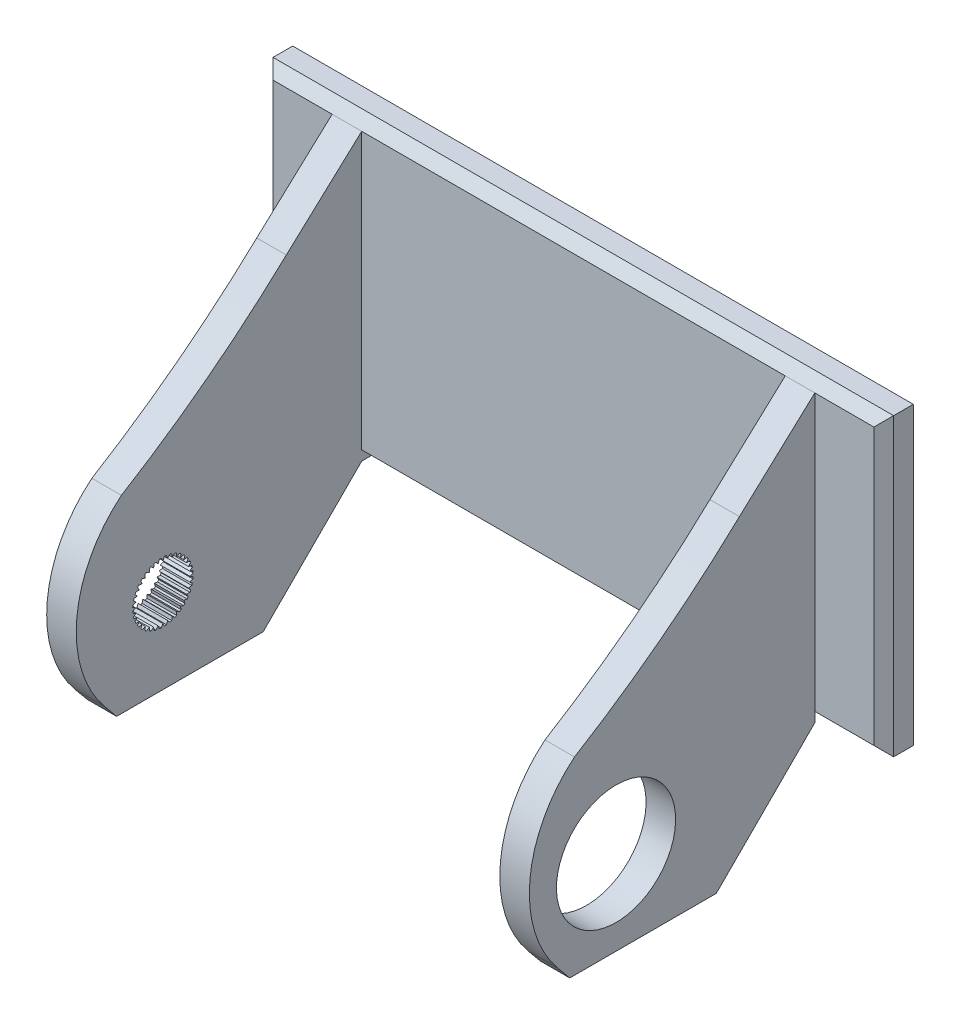
SolidWorks part; units mm, degrees
material "PLA"
ref_plane "Front Plane" through (0, 0, 0) normal (0, 0, 1) x (1, 0, 0)
ref_plane "Top Plane" through (0, 0, 0) normal (0, 1, 0) x (1, 0, 0)
ref_plane "Right Plane" through (0, 0, 0) normal (1, 0, 0) x (0, 0, -1)
sketch "Sketch2" plane through (0, 0, 0) normal (0, 0, 1) x (1, 0, 0)
  line L1 (-31.5, -15) -> (31.5, -15)
  line L2 (-31.5, -15) -> (-31.5, 15)
  line L3 (-31.5, 15) -> (31.5, 15)
  line L4 (31.5, -15) -> (31.5, 15)
  point P4 (0, 15)
  point P6 (-31.5, 0)
  dimension "D1" = 63
  dimension "D2" = 30
extrude "Boss-Extrude2" add sketch "Sketch2" along normal blind 3
sketch "Sketch6" plane through (0, 0, 3) normal (0, 0, 1) x (1, 0, 0)
  line L0 (31.5, 15) -> (-31.5, 15) construction
  line L1 (-24.5, 15) -> (-21.5, 15)
  line L3 (-24.5, -15) -> (-21.5, -15)
  line L4 (-21.5, 15) -> (-21.5, -15)
  line L5 (-31.5, -15) -> (31.5, -15) construction
  line L7 (-24.5, 15) -> (-24.5, -15)
  dimension "D1" = 3
extrude "Boss-Extrude5" add sketch "Sketch6" along normal blind 20
sketch "Sketch7" plane through (0, -15, 0) normal (0, -1, 0) x (1, 0, 0)
  line L0 (-31.5, 0) -> (31.5, 0) construction
  line L1 (-24.5, 23) -> (-21.5, 23)
  line L2 (-24.5, 23) -> (-24.5, 0)
  line L3 (-24.5, 0) -> (-21.5, 0)
  line L4 (-21.5, 23) -> (-21.5, 0)
  dimension "D1" = 3
extrude "Boss-Extrude6" add sketch "Sketch7" along normal blind 10
sketch "Sketch8" plane through (0, 0, 23) normal (0, 0, 1) x (1, 0, 0)
  line L4 (-24.5, 15) -> (-24.5, -25)
  line L5 (-24.5, 15) -> (-24.5, -25)
  line L7 (-24.5, -25) -> (-21.5, -25)
  line L8 (-21.5, -25) -> (-21.5, 15)
  line L11 (-21.5, 15) -> (-24.5, 15)
  line L13 (-24.5, -25) -> (-21.5, -25)
  line L14 (-21.5, -25) -> (-21.5, 15)
  line L17 (-21.5, 15) -> (-24.5, 15)
  dimension "D1" = 0
extrude "Boss-Extrude7" add sketch "Sketch8" along normal blind 15
sketch "Sketch9" plane through (-24.5, 0, 0) normal (-1, 0, 0) x (0, 0, 1)
  line L288 (25.551, -14.882) -> (25.5973, -14.8018) construction
  line L289 (25.5298, -14.7054) -> (25.4386, -14.7215) construction
  line L290 (25.5973, -14.8018) -> (25.6299, -14.7454) construction
  line L291 (25.5939, -14.6941) -> (25.5298, -14.7054) construction
  line L292 (25.4711, -15.0204) -> (25.551, -14.882) construction
  line L293 (25.4386, -14.7215) -> (25.2812, -14.7493) construction
  line L294 (25.279, -14.4066) -> (25.3013, -14.3454) construction
  line L295 (25.257, -14.3011) -> (25.1958, -14.3233) construction
  line L296 (25.2473, -14.4936) -> (25.279, -14.4066) construction
  line L297 (25.1958, -14.3233) -> (25.1088, -14.355) construction
  line L298 (25.1927, -14.6438) -> (25.2473, -14.4936) construction
  line L299 (25.1088, -14.355) -> (24.9586, -14.4097) construction
  line L300 (24.8569, -13.9725) -> (24.8005, -14.0051) construction
  line L301 (24.8969, -14.0726) -> (24.9082, -14.0084) construction
  line L302 (24.8005, -14.0051) -> (24.7203, -14.0514) construction
  line L303 (24.8808, -14.1638) -> (24.8969, -14.0726) construction
  line L304 (24.7203, -14.0514) -> (24.5819, -14.1313) construction
  line L305 (24.8531, -14.3211) -> (24.8808, -14.1638) construction
  line L306 (25.6799, -15.4397) -> (25.7826, -15.3173) construction
  line L307 (25.6998, -15.1397) -> (25.54, -15.1397) construction
  line L308 (25.8421, -15.2464) -> (25.884, -15.1965) construction
  line L309 (25.8575, -15.1397) -> (25.7924, -15.1397) construction
  line L310 (25.7826, -15.3173) -> (25.8421, -15.2464) construction
  line L311 (25.7924, -15.1397) -> (25.6998, -15.1397) construction
  line L312 (26.006, -15.7267) -> (26.0559, -15.6848) construction
  line L313 (26.0397, -15.6243) -> (25.9756, -15.613) construction
  line L314 (25.9351, -15.7862) -> (26.006, -15.7267) construction
  line L315 (25.9756, -15.613) -> (25.8843, -15.5969) construction
  line L316 (25.8126, -15.8889) -> (25.9351, -15.7862) construction
  line L317 (25.8843, -15.5969) -> (25.727, -15.5692) construction
  line L318 (25.8654, -16.3543) -> (26.0038, -16.2744) construction
  line L319 (25.9867, -16.0792) -> (25.8366, -16.0246) construction
  line L320 (26.0038, -16.2744) -> (26.084, -16.2281) construction
  line L321 (26.0738, -16.1109) -> (25.9867, -16.0792) construction
  line L322 (26.084, -16.2281) -> (26.1404, -16.1956) construction
  line L323 (26.1349, -16.1332) -> (26.0738, -16.1109) construction
  line L324 (26.1404, -16.6509) -> (26.084, -16.6183) construction
  line L325 (26.0738, -16.7355) -> (26.1349, -16.7133) construction
  line L326 (26.084, -16.6183) -> (26.0038, -16.572) construction
  line L327 (25.9867, -16.7672) -> (26.0738, -16.7355) construction
  line L328 (26.0038, -16.572) -> (25.8654, -16.4921) construction
  line L329 (25.8366, -16.8219) -> (25.9867, -16.7672) construction
  line L330 (25.9756, -17.2334) -> (26.0397, -17.2221) construction
  line L331 (26.0559, -17.1616) -> (26.006, -17.1198) construction
  line L332 (25.8843, -17.2495) -> (25.9756, -17.2334) construction
  line L333 (26.006, -17.1198) -> (25.9351, -17.0602) construction
  line L334 (25.727, -17.2773) -> (25.8843, -17.2495) construction
  line L335 (25.9351, -17.0602) -> (25.8126, -16.9575) construction
  line L336 (25.6998, -17.7067) -> (25.7924, -17.7067) construction
  line L337 (25.8421, -17.6001) -> (25.7826, -17.5291) construction
  line L338 (25.54, -17.7067) -> (25.6998, -17.7067) construction
  line L339 (25.7826, -17.5291) -> (25.6799, -17.4067) construction
  line L340 (25.8654, -16.4921) -> (25.7461, -16.4232) construction
  line L341 (25.7461, -16.4232) -> (25.8654, -16.3543) construction
  line L342 (25.8366, -16.0246) -> (25.7071, -15.9775) construction
  line L343 (25.7071, -15.9775) -> (25.8126, -15.8889) construction
  line L344 (25.727, -15.5692) -> (25.5913, -15.5453) construction
  line L345 (25.5913, -15.5453) -> (25.6799, -15.4397) construction
  line L346 (25.54, -15.1397) -> (25.4022, -15.1397) construction
  line L347 (25.4022, -15.1397) -> (25.4711, -15.0204) construction
  line L348 (25.2812, -14.7493) -> (25.1456, -14.7732) construction
  line L349 (25.1456, -14.7732) -> (25.1927, -14.6438) construction
  line L350 (24.9586, -14.4097) -> (24.8292, -14.4568) construction
  line L351 (24.8292, -14.4568) -> (24.8531, -14.3211) construction
  line L352 (24.5819, -14.1313) -> (24.4626, -14.2001) construction
  line L353 (24.4626, -14.2001) -> (24.4626, -14.0624) construction
  line L354 (24.1626, -13.9225) -> (24.0571, -14.011) construction
  line L355 (24.0571, -14.011) -> (24.0332, -13.8754) construction
  line L356 (23.7134, -13.7897) -> (23.6249, -13.8952) construction
  line L357 (23.6249, -13.8952) -> (23.5778, -13.7658) construction
  line L358 (23.248, -13.7369) -> (23.1791, -13.8562) construction
  line L359 (23.1791, -13.8562) -> (23.1103, -13.7369) construction
  line L360 (22.7805, -13.7658) -> (22.7334, -13.8952) construction
  line L361 (22.7334, -13.8952) -> (22.6449, -13.7897) construction
  line L362 (22.3251, -13.8754) -> (22.3012, -14.011) construction
  line L363 (22.3012, -14.011) -> (22.1957, -13.9225) construction
  line L364 (21.8957, -14.0624) -> (21.8957, -14.2001) construction
  line L365 (21.8957, -14.2001) -> (21.7764, -14.1313) construction
  line L366 (21.5052, -14.3211) -> (21.5291, -14.4568) construction
  line L367 (21.5291, -14.4568) -> (21.3997, -14.4097) construction
  line L368 (21.1656, -14.6438) -> (21.2127, -14.7732) construction
  line L369 (21.2127, -14.7732) -> (21.0771, -14.7493) construction
  line L370 (20.8872, -15.0204) -> (20.9561, -15.1397) construction
  line L371 (20.9561, -15.1397) -> (20.8183, -15.1397) construction
  line L372 (20.6784, -15.4397) -> (20.767, -15.5453) construction
  line L373 (20.767, -15.5453) -> (20.6313, -15.5692) construction
  line L374 (20.5456, -15.8889) -> (20.6512, -15.9775) construction
  line L375 (20.6512, -15.9775) -> (20.5217, -16.0246) construction
  line L376 (20.4929, -16.3543) -> (20.6122, -16.4232) construction
  line L377 (20.6122, -16.4232) -> (20.4929, -16.4921) construction
  line L378 (20.5217, -16.8219) -> (20.6512, -16.869) construction
  line L379 (20.6512, -16.869) -> (20.5456, -16.9575) construction
  line L380 (20.6313, -17.2773) -> (20.767, -17.3012) construction
  line L381 (20.767, -17.3012) -> (20.6784, -17.4067) construction
  line L382 (20.8183, -17.7067) -> (20.9561, -17.7067) construction
  line L383 (20.9561, -17.7067) -> (20.8872, -17.826) construction
  line L384 (21.0771, -18.0972) -> (21.2127, -18.0732) construction
  line L385 (21.2127, -18.0732) -> (21.1656, -18.2027) construction
  line L386 (21.3997, -18.4368) -> (21.5291, -18.3896) construction
  line L387 (21.5291, -18.3896) -> (21.5052, -18.5253) construction
  line L388 (21.7764, -18.7152) -> (21.8957, -18.6463) construction
  line L389 (21.8957, -18.6463) -> (21.8957, -18.784) construction
  line L390 (22.1957, -18.9239) -> (22.3012, -18.8354) construction
  line L391 (22.3012, -18.8354) -> (22.3251, -18.971) construction
  line L392 (22.6449, -19.0567) -> (22.7334, -18.9512) construction
  line L393 (22.7334, -18.9512) -> (22.7805, -19.0806) construction
  line L394 (23.1103, -19.1095) -> (23.1791, -18.9902) construction
  line L395 (23.1791, -18.9902) -> (23.248, -19.1095) construction
  line L396 (23.5778, -19.0806) -> (23.6249, -18.9512) construction
  line L397 (23.6249, -18.9512) -> (23.7134, -19.0567) construction
  line L398 (24.0332, -18.971) -> (24.0571, -18.8354) construction
  line L399 (24.0571, -18.8354) -> (24.1626, -18.9239) construction
  line L400 (24.4626, -18.784) -> (24.4626, -18.6463) construction
  line L401 (24.4626, -18.6463) -> (24.5819, -18.7152) construction
  line L402 (24.8531, -18.5253) -> (24.8292, -18.3896) construction
  line L403 (24.8292, -18.3896) -> (24.9586, -18.4368) construction
  line L404 (25.1927, -18.2027) -> (25.1456, -18.0732) construction
  line L405 (25.1456, -18.0732) -> (25.2812, -18.0972) construction
  line L406 (25.4711, -17.826) -> (25.4022, -17.7067) construction
  line L407 (25.4022, -17.7067) -> (25.54, -17.7067) construction
  line L408 (25.6799, -17.4067) -> (25.5913, -17.3012) construction
  line L409 (25.5913, -17.3012) -> (25.727, -17.2773) construction
  line L410 (25.8126, -16.9575) -> (25.7071, -16.869) construction
  line L411 (25.7071, -16.869) -> (25.8366, -16.8219) construction
  line L412 (25.7924, -17.7067) -> (25.8575, -17.7067) construction
  line L413 (25.884, -17.6499) -> (25.8421, -17.6001) construction
  line L414 (25.6299, -18.101) -> (25.5973, -18.0446) construction
  line L415 (25.5298, -18.141) -> (25.5939, -18.1523) construction
  line L416 (25.5973, -18.0446) -> (25.551, -17.9644) construction
  line L417 (25.4386, -18.1249) -> (25.5298, -18.141) construction
  line L418 (24.9586, -18.4368) -> (25.1088, -18.4914) construction
  line L419 (25.2473, -18.3528) -> (25.1927, -18.2027) construction
  line L420 (25.1088, -18.4914) -> (25.1958, -18.5231) construction
  line L421 (25.279, -18.4399) -> (25.2473, -18.3528) construction
  line L422 (25.1958, -18.5231) -> (25.257, -18.5454) construction
  line L423 (25.3013, -18.5011) -> (25.279, -18.4399) construction
  line L424 (25.551, -17.9644) -> (25.4711, -17.826) construction
  line L425 (25.2812, -18.0972) -> (25.4386, -18.1249) construction
  line L426 (24.9082, -18.838) -> (24.8969, -18.7739) construction
  line L427 (24.8005, -18.8414) -> (24.8569, -18.8739) construction
  line L428 (24.8969, -18.7739) -> (24.8808, -18.6827) construction
  line L429 (24.7203, -18.7951) -> (24.8005, -18.8414) construction
  line L430 (24.8808, -18.6827) -> (24.8531, -18.5253) construction
  line L431 (24.5819, -18.7152) -> (24.7203, -18.7951) construction
  line L432 (22.8668, -19.3178) -> (22.8891, -19.379) construction
  line L433 (22.9515, -19.3845) -> (22.9841, -19.3281) construction
  line L434 (22.8352, -19.2308) -> (22.8668, -19.3178) construction
  line L435 (22.9841, -19.3281) -> (23.0304, -19.2479) construction
  line L436 (23.5231, -19.2308) -> (23.5778, -19.0806) construction
  line L437 (23.248, -19.1095) -> (23.3279, -19.2479) construction
  line L438 (23.4915, -19.3178) -> (23.5231, -19.2308) construction
  line L439 (23.3279, -19.2479) -> (23.3742, -19.3281) construction
  line L440 (23.4692, -19.379) -> (23.4915, -19.3178) construction
  line L441 (23.3742, -19.3281) -> (23.4068, -19.3845) construction
  line L442 (23.8757, -19.2501) -> (23.9175, -19.3) construction
  line L443 (23.978, -19.2838) -> (23.9894, -19.2196) construction
  line L444 (24.356, -19.0862) -> (24.4059, -19.128) construction
  line L445 (24.4626, -19.1016) -> (24.4626, -19.0365) construction
  line L446 (24.285, -19.0267) -> (24.356, -19.0862) construction
  line L447 (24.4626, -19.0365) -> (24.4626, -18.9438) construction
  line L448 (24.1626, -18.9239) -> (24.285, -19.0267) construction
  line L449 (24.4626, -18.9438) -> (24.4626, -18.784) construction
  line L450 (23.8162, -19.1791) -> (23.8757, -19.2501) construction
  line L451 (23.9894, -19.2196) -> (24.0054, -19.1284) construction
  line L452 (23.7134, -19.0567) -> (23.8162, -19.1791) construction
  line L453 (24.0054, -19.1284) -> (24.0332, -18.971) construction
  line L454 (22.7805, -19.0806) -> (22.8352, -19.2308) construction
  line L455 (23.0304, -19.2479) -> (23.1103, -19.1095) construction
  line L456 (22.3689, -19.2196) -> (22.3802, -19.2838) construction
  line L457 (22.4407, -19.3) -> (22.4826, -19.2501) construction
  line L458 (22.3529, -19.1284) -> (22.3689, -19.2196) construction
  line L459 (22.4826, -19.2501) -> (22.5421, -19.1791) construction
  line L460 (22.3251, -18.971) -> (22.3529, -19.1284) construction
  line L461 (22.5421, -19.1791) -> (22.6449, -19.0567) construction
  line L462 (21.8957, -19.0365) -> (21.8957, -19.1016) construction
  line L463 (21.9524, -19.128) -> (22.0023, -19.0862) construction
  line L464 (21.8957, -18.9438) -> (21.8957, -19.0365) construction
  line L465 (22.0023, -19.0862) -> (22.0733, -19.0267) construction
  line L466 (21.8957, -18.784) -> (21.8957, -18.9438) construction
  line L467 (22.0733, -19.0267) -> (22.1957, -18.9239) construction
  line L468 (21.4614, -18.7739) -> (21.4501, -18.838) construction
  line L469 (21.5014, -18.8739) -> (21.5578, -18.8414) construction
  line L470 (21.4775, -18.6827) -> (21.4614, -18.7739) construction
  line L471 (21.5578, -18.8414) -> (21.638, -18.7951) construction
  line L472 (21.5052, -18.5253) -> (21.4775, -18.6827) construction
  line L473 (21.638, -18.7951) -> (21.7764, -18.7152) construction
  line L474 (21.0793, -18.4399) -> (21.057, -18.5011) construction
  line L475 (21.1013, -18.5454) -> (21.1625, -18.5231) construction
  line L476 (21.111, -18.3528) -> (21.0793, -18.4399) construction
  line L477 (21.1625, -18.5231) -> (21.2495, -18.4914) construction
  line L478 (21.1656, -18.2027) -> (21.111, -18.3528) construction
  line L479 (21.2495, -18.4914) -> (21.3997, -18.4368) construction
  line L480 (20.7644, -18.1523) -> (20.8285, -18.141) construction
  line L481 (20.761, -18.0446) -> (20.7284, -18.101) construction
  line L482 (20.8285, -18.141) -> (20.9197, -18.1249) construction
  line L483 (20.8073, -17.9644) -> (20.761, -18.0446) construction
  line L484 (20.9197, -18.1249) -> (21.0771, -18.0972) construction
  line L485 (20.8872, -17.826) -> (20.8073, -17.9644) construction
  line L486 (20.5008, -17.7067) -> (20.5659, -17.7067) construction
  line L487 (20.5162, -17.6001) -> (20.4743, -17.6499) construction
  line L488 (20.5659, -17.7067) -> (20.6585, -17.7067) construction
  line L489 (20.5757, -17.5291) -> (20.5162, -17.6001) construction
  line L490 (20.6585, -17.7067) -> (20.8183, -17.7067) construction
  line L491 (20.6784, -17.4067) -> (20.5757, -17.5291) construction
  line L492 (20.3186, -17.2221) -> (20.3827, -17.2334) construction
  line L493 (20.3523, -17.1198) -> (20.3024, -17.1616) construction
  line L494 (20.3827, -17.2334) -> (20.4739, -17.2495) construction
  line L495 (20.4232, -17.0602) -> (20.3523, -17.1198) construction
  line L496 (20.4739, -17.2495) -> (20.6313, -17.2773) construction
  line L497 (20.5456, -16.9575) -> (20.4232, -17.0602) construction
  line L498 (20.2233, -16.7133) -> (20.2845, -16.7355) construction
  line L499 (20.2743, -16.6183) -> (20.2179, -16.6509) construction
  line L500 (20.3716, -16.7672) -> (20.5217, -16.8219) construction
  line L501 (20.4929, -16.4921) -> (20.3545, -16.572) construction
  line L502 (20.2845, -16.7355) -> (20.3716, -16.7672) construction
  line L503 (20.3545, -16.572) -> (20.2743, -16.6183) construction
  line L504 (20.2179, -16.1956) -> (20.2743, -16.2281) construction
  line L505 (20.2845, -16.1109) -> (20.2233, -16.1332) construction
  line L506 (20.2743, -16.2281) -> (20.3545, -16.2744) construction
  line L507 (20.3716, -16.0792) -> (20.2845, -16.1109) construction
  line L508 (20.3545, -16.2744) -> (20.4929, -16.3543) construction
  line L509 (20.5217, -16.0246) -> (20.3716, -16.0792) construction
  line L510 (20.3523, -15.7267) -> (20.4232, -15.7862) construction
  line L511 (20.4739, -15.5969) -> (20.3827, -15.613) construction
  line L512 (20.3024, -15.6848) -> (20.3523, -15.7267) construction
  line L513 (20.3827, -15.613) -> (20.3186, -15.6243) construction
  line L514 (20.4232, -15.7862) -> (20.5456, -15.8889) construction
  line L515 (20.6313, -15.5692) -> (20.4739, -15.5969) construction
  line L516 (20.5162, -15.2464) -> (20.5757, -15.3173) construction
  line L517 (20.6585, -15.1397) -> (20.5659, -15.1397) construction
  line L518 (20.4743, -15.1965) -> (20.5162, -15.2464) construction
  line L519 (20.5659, -15.1397) -> (20.5008, -15.1397) construction
  line L520 (20.5757, -15.3173) -> (20.6784, -15.4397) construction
  line L521 (20.8183, -15.1397) -> (20.6585, -15.1397) construction
  line L522 (20.7284, -14.7454) -> (20.761, -14.8018) construction
  line L523 (20.8285, -14.7054) -> (20.7644, -14.6941) construction
  line L524 (20.761, -14.8018) -> (20.8073, -14.882) construction
  line L525 (20.9197, -14.7215) -> (20.8285, -14.7054) construction
  line L526 (20.8073, -14.882) -> (20.8872, -15.0204) construction
  line L527 (21.0771, -14.7493) -> (20.9197, -14.7215) construction
  line L528 (21.1625, -14.3233) -> (21.1013, -14.3011) construction
  line L529 (21.057, -14.3454) -> (21.0793, -14.4066) construction
  line L530 (21.2495, -14.355) -> (21.1625, -14.3233) construction
  line L531 (21.0793, -14.4066) -> (21.111, -14.4936) construction
  line L532 (21.3997, -14.4097) -> (21.2495, -14.355) construction
  line L533 (21.111, -14.4936) -> (21.1656, -14.6438) construction
  line L534 (21.4501, -14.0084) -> (21.4614, -14.0726) construction
  line L535 (21.5578, -14.0051) -> (21.5014, -13.9725) construction
  line L536 (21.4614, -14.0726) -> (21.4775, -14.1638) construction
  line L537 (21.638, -14.0514) -> (21.5578, -14.0051) construction
  line L538 (21.4775, -14.1638) -> (21.5052, -14.3211) construction
  line L539 (21.7764, -14.1313) -> (21.638, -14.0514) construction
  line L540 (21.8957, -13.7449) -> (21.8957, -13.81) construction
  line L541 (22.0023, -13.7602) -> (21.9524, -13.7184) construction
  line L542 (21.8957, -13.81) -> (21.8957, -13.9026) construction
  line L543 (22.0733, -13.8198) -> (22.0023, -13.7602) construction
  line L544 (21.8957, -13.9026) -> (21.8957, -14.0624) construction
  line L545 (22.1957, -13.9225) -> (22.0733, -13.8198) construction
  line L546 (22.3802, -13.5627) -> (22.3689, -13.6268) construction
  line L547 (22.4826, -13.5963) -> (22.4407, -13.5465) construction
  line L548 (22.3689, -13.6268) -> (22.3529, -13.718) construction
  line L549 (22.5421, -13.6673) -> (22.4826, -13.5963) construction
  line L550 (22.3529, -13.718) -> (22.3251, -13.8754) construction
  line L551 (22.6449, -13.7897) -> (22.5421, -13.6673) construction
  line L552 (24.356, -13.7602) -> (24.285, -13.8198) construction
  line L553 (24.4626, -13.9026) -> (24.4626, -13.81) construction
  line L554 (24.4059, -13.7184) -> (24.356, -13.7602) construction
  line L555 (24.4626, -13.81) -> (24.4626, -13.7449) construction
  line L556 (24.285, -13.8198) -> (24.1626, -13.9225) construction
  line L557 (24.4626, -14.0624) -> (24.4626, -13.9026) construction
  line L558 (23.9894, -13.6268) -> (23.978, -13.5627) construction
  line L559 (23.9175, -13.5465) -> (23.8757, -13.5963) construction
  line L560 (24.0054, -13.718) -> (23.9894, -13.6268) construction
  line L561 (23.8757, -13.5963) -> (23.8162, -13.6673) construction
  line L562 (24.0332, -13.8754) -> (24.0054, -13.718) construction
  line L563 (23.8162, -13.6673) -> (23.7134, -13.7897) construction
  line L564 (23.4915, -13.5286) -> (23.4692, -13.4674) construction
  line L565 (23.4068, -13.462) -> (23.3742, -13.5183) construction
  line L566 (23.5231, -13.6156) -> (23.4915, -13.5286) construction
  line L567 (23.3742, -13.5183) -> (23.3279, -13.5986) construction
  line L568 (23.5778, -13.7658) -> (23.5231, -13.6156) construction
  line L569 (23.3279, -13.5986) -> (23.248, -13.7369) construction
  line L570 (22.8891, -13.4674) -> (22.8668, -13.5286) construction
  line L571 (22.9841, -13.5183) -> (22.9515, -13.462) construction
  line L572 (22.8668, -13.5286) -> (22.8352, -13.6156) construction
  line L573 (23.0304, -13.5986) -> (22.9841, -13.5183) construction
  line L574 (22.8352, -13.6156) -> (22.7805, -13.7658) construction
  line L575 (23.1103, -13.7369) -> (23.0304, -13.5986) construction
  line L576 (25.6376, -14.932) -> (25.6839, -14.8518)
  line L577 (25.6839, -14.8518) -> (25.7476, -14.7415)
  line L578 (25.6379, -14.5848) -> (25.5124, -14.607)
  line L579 (25.5124, -14.607) -> (25.4212, -14.623)
  line L580 (25.4212, -14.623) -> (25.2988, -14.6446)
  line L581 (25.2988, -14.6446) -> (25.3413, -14.5278)
  line L582 (25.3413, -14.5278) -> (25.373, -14.4408)
  line L583 (25.373, -14.4408) -> (25.4165, -14.3211)
  line L584 (25.2813, -14.1858) -> (25.1616, -14.2294)
  line L585 (25.1616, -14.2294) -> (25.0746, -14.2611)
  line L586 (25.0746, -14.2611) -> (24.9577, -14.3036)
  line L587 (24.9577, -14.3036) -> (24.9793, -14.1811)
  line L588 (24.9793, -14.1811) -> (24.9954, -14.0899)
  line L589 (24.9954, -14.0899) -> (25.0175, -13.9645)
  line L590 (24.8608, -13.8548) -> (24.7505, -13.9185)
  line L591 (24.7505, -13.9185) -> (24.6703, -13.9648)
  line L592 (24.6703, -13.9648) -> (24.5626, -14.0269)
  line L593 (24.5626, -14.0269) -> (24.5626, -13.9026)
  line L594 (24.5626, -13.9026) -> (24.5626, -13.81)
  line L595 (24.5626, -13.81) -> (24.5626, -13.6826)
  line L596 (24.3893, -13.6018) -> (24.2917, -13.6836)
  line L597 (24.2917, -13.6836) -> (24.2208, -13.7432)
  line L598 (24.2208, -13.7432) -> (24.1255, -13.8231)
  line L599 (24.1255, -13.8231) -> (24.1039, -13.7007)
  line L600 (24.1039, -13.7007) -> (24.0878, -13.6094)
  line L601 (24.0878, -13.6094) -> (24.0657, -13.484)
  line L602 (23.8809, -13.4345) -> (23.7991, -13.5321)
  line L603 (23.7991, -13.5321) -> (23.7395, -13.603)
  line L604 (23.7395, -13.603) -> (23.6596, -13.6983)
  line L605 (23.6596, -13.6983) -> (23.6171, -13.5814)
  line L606 (23.6171, -13.5814) -> (23.5854, -13.4944)
  line L607 (23.5854, -13.4944) -> (23.5419, -13.3747)
  line L608 (23.3513, -13.358) -> (23.2876, -13.4683)
  line L609 (23.2876, -13.4683) -> (23.2413, -13.5486)
  line L610 (23.2413, -13.5486) -> (23.1791, -13.6562)
  line L611 (23.1791, -13.6562) -> (23.117, -13.5486)
  line L612 (23.117, -13.5486) -> (23.0707, -13.4683)
  line L613 (23.0707, -13.4683) -> (23.007, -13.358)
  line L614 (22.8164, -13.3747) -> (22.7729, -13.4944)
  line L615 (22.7729, -13.4944) -> (22.7412, -13.5814)
  line L616 (22.7412, -13.5814) -> (22.6987, -13.6983)
  line L617 (22.6987, -13.6983) -> (22.6187, -13.603)
  line L618 (22.6187, -13.603) -> (22.5592, -13.5321)
  line L619 (22.5592, -13.5321) -> (22.4773, -13.4345)
  line L620 (22.2926, -13.484) -> (22.2705, -13.6094)
  line L621 (22.2705, -13.6094) -> (22.2544, -13.7007)
  line L622 (22.2544, -13.7007) -> (22.2328, -13.8231)
  line L623 (22.2328, -13.8231) -> (22.1375, -13.7432)
  line L624 (22.1375, -13.7432) -> (22.0666, -13.6836)
  line L625 (22.0666, -13.6836) -> (21.969, -13.6018)
  line L626 (21.7957, -13.6826) -> (21.7957, -13.81)
  line L627 (21.7957, -13.81) -> (21.7957, -13.9026)
  line L628 (21.7957, -13.9026) -> (21.7957, -14.0269)
  line L629 (21.7957, -14.0269) -> (21.688, -13.9648)
  line L630 (21.688, -13.9648) -> (21.6078, -13.9185)
  line L631 (21.6078, -13.9185) -> (21.4975, -13.8548)
  line L632 (21.3408, -13.9645) -> (21.3629, -14.0899)
  line L633 (21.3629, -14.0899) -> (21.379, -14.1811)
  line L634 (21.379, -14.1811) -> (21.4006, -14.3036)
  line L635 (21.4006, -14.3036) -> (21.2837, -14.2611)
  line L636 (21.2837, -14.2611) -> (21.1967, -14.2294)
  line L637 (21.1967, -14.2294) -> (21.077, -14.1858)
  line L638 (20.9417, -14.3211) -> (20.9853, -14.4408)
  line L639 (20.9853, -14.4408) -> (21.017, -14.5278)
  line L640 (21.017, -14.5278) -> (21.0595, -14.6446)
  line L641 (21.0595, -14.6446) -> (20.9371, -14.623)
  line L642 (20.9371, -14.623) -> (20.8458, -14.607)
  line L643 (20.8458, -14.607) -> (20.7204, -14.5848)
  line L644 (20.6107, -14.7415) -> (20.6744, -14.8518)
  line L645 (20.6744, -14.8518) -> (20.7207, -14.932)
  line L646 (20.7207, -14.932) -> (20.7829, -15.0397)
  line L647 (20.7829, -15.0397) -> (20.6585, -15.0397)
  line L648 (20.6585, -15.0397) -> (20.5659, -15.0397)
  line L649 (20.5659, -15.0397) -> (20.4386, -15.0397)
  line L650 (20.3577, -15.2131) -> (20.4396, -15.3107)
  line L651 (20.4396, -15.3107) -> (20.4991, -15.3816)
  line L652 (20.4991, -15.3816) -> (20.579, -15.4769)
  line L653 (20.579, -15.4769) -> (20.4566, -15.4984)
  line L654 (20.4566, -15.4984) -> (20.3654, -15.5145)
  line L655 (20.3654, -15.5145) -> (20.2399, -15.5366)
  line L656 (20.1904, -15.7214) -> (20.288, -15.8033)
  line L657 (20.288, -15.8033) -> (20.3589, -15.8628)
  line L658 (20.3589, -15.8628) -> (20.4542, -15.9427)
  line L659 (20.4542, -15.9427) -> (20.3374, -15.9853)
  line L660 (20.3374, -15.9853) -> (20.2503, -16.0169)
  line L661 (20.2503, -16.0169) -> (20.1306, -16.0605)
  line L662 (20.114, -16.2511) -> (20.2243, -16.3147)
  line L663 (20.2243, -16.3147) -> (20.3045, -16.3611)
  line L664 (20.3045, -16.3611) -> (20.4122, -16.4232)
  line L665 (20.4122, -16.4232) -> (20.3045, -16.4854)
  line L666 (20.3045, -16.4854) -> (20.2243, -16.5317)
  line L667 (20.2243, -16.5317) -> (20.114, -16.5954)
  line L668 (20.1306, -16.7859) -> (20.2503, -16.8295)
  line L669 (20.2503, -16.8295) -> (20.3374, -16.8612)
  line L670 (20.3374, -16.8612) -> (20.4542, -16.9037)
  line L671 (20.4542, -16.9037) -> (20.3589, -16.9836)
  line L672 (20.3589, -16.9836) -> (20.288, -17.0432)
  line L673 (20.288, -17.0432) -> (20.1904, -17.125)
  line L674 (20.2399, -17.3098) -> (20.3654, -17.3319)
  line L675 (20.3654, -17.3319) -> (20.4566, -17.348)
  line L676 (20.4566, -17.348) -> (20.579, -17.3696)
  line L677 (20.579, -17.3696) -> (20.4991, -17.4648)
  line L678 (20.4991, -17.4648) -> (20.4396, -17.5358)
  line L679 (20.4396, -17.5358) -> (20.3577, -17.6333)
  line L680 (20.4386, -17.8067) -> (20.5659, -17.8067)
  line L681 (20.5659, -17.8067) -> (20.6585, -17.8067)
  line L682 (20.6585, -17.8067) -> (20.7829, -17.8067)
  line L683 (20.7829, -17.8067) -> (20.7207, -17.9144)
  line L684 (20.7207, -17.9144) -> (20.6744, -17.9946)
  line L685 (20.6744, -17.9946) -> (20.6107, -18.1049)
  line L686 (20.7204, -18.2616) -> (20.8458, -18.2395)
  line L687 (20.8458, -18.2395) -> (20.9371, -18.2234)
  line L688 (20.9371, -18.2234) -> (21.0595, -18.2018)
  line L689 (21.0595, -18.2018) -> (21.017, -18.3186)
  line L690 (21.017, -18.3186) -> (20.9853, -18.4057)
  line L691 (20.9853, -18.4057) -> (20.9417, -18.5253)
  line L692 (21.077, -18.6606) -> (21.1967, -18.6171)
  line L693 (21.1967, -18.6171) -> (21.2837, -18.5854)
  line L694 (21.2837, -18.5854) -> (21.4006, -18.5429)
  line L695 (21.4006, -18.5429) -> (21.379, -18.6653)
  line L696 (21.379, -18.6653) -> (21.3629, -18.7565)
  line L697 (21.3629, -18.7565) -> (21.3408, -18.8819)
  line L698 (21.4975, -18.9917) -> (21.6078, -18.928)
  line L699 (21.6078, -18.928) -> (21.688, -18.8817)
  line L700 (21.688, -18.8817) -> (21.7957, -18.8195)
  line L701 (21.7957, -18.8195) -> (21.7957, -18.9438)
  line L702 (21.7957, -18.9438) -> (21.7957, -19.0365)
  line L703 (21.7957, -19.0365) -> (21.7957, -19.1638)
  line L704 (21.969, -19.2447) -> (22.0666, -19.1628)
  line L705 (22.0666, -19.1628) -> (22.1375, -19.1033)
  line L706 (22.1375, -19.1033) -> (22.2328, -19.0233)
  line L707 (22.2328, -19.0233) -> (22.2544, -19.1458)
  line L708 (22.2544, -19.1458) -> (22.2705, -19.237)
  line L709 (22.2705, -19.237) -> (22.2926, -19.3624)
  line L710 (22.4773, -19.4119) -> (22.5592, -19.3144)
  line L711 (22.5592, -19.3144) -> (22.6187, -19.2434)
  line L712 (22.6187, -19.2434) -> (22.6987, -19.1482)
  line L713 (22.6987, -19.1482) -> (22.7412, -19.265)
  line L714 (22.7412, -19.265) -> (22.7729, -19.352)
  line L715 (22.7729, -19.352) -> (22.8164, -19.4717)
  line L716 (23.007, -19.4884) -> (23.0707, -19.3781)
  line L717 (23.0707, -19.3781) -> (23.117, -19.2979)
  line L718 (23.117, -19.2979) -> (23.1791, -19.1902)
  line L719 (23.1791, -19.1902) -> (23.2413, -19.2979)
  line L720 (23.2413, -19.2979) -> (23.2876, -19.3781)
  line L721 (23.2876, -19.3781) -> (23.3513, -19.4884)
  line L722 (23.5419, -19.4717) -> (23.5854, -19.352)
  line L723 (23.5854, -19.352) -> (23.6171, -19.265)
  line L724 (23.6171, -19.265) -> (23.6596, -19.1482)
  line L725 (23.6596, -19.1482) -> (23.7395, -19.2434)
  line L726 (23.7395, -19.2434) -> (23.7991, -19.3144)
  line L727 (23.7991, -19.3144) -> (23.8809, -19.4119)
  line L728 (24.0657, -19.3624) -> (24.0878, -19.237)
  line L729 (24.0878, -19.237) -> (24.1039, -19.1458)
  line L730 (24.1039, -19.1458) -> (24.1255, -19.0233)
  line L731 (24.1255, -19.0233) -> (24.2208, -19.1033)
  line L732 (24.2208, -19.1033) -> (24.2917, -19.1628)
  line L733 (24.2917, -19.1628) -> (24.3893, -19.2447)
  line L734 (24.5626, -19.1638) -> (24.5626, -19.0365)
  line L735 (24.5626, -19.0365) -> (24.5626, -18.9438)
  line L736 (24.5626, -18.9438) -> (24.5626, -18.8195)
  line L737 (24.5626, -18.8195) -> (24.6703, -18.8817)
  line L738 (24.6703, -18.8817) -> (24.7505, -18.928)
  line L739 (24.7505, -18.928) -> (24.8608, -18.9917)
  line L740 (25.0175, -18.8819) -> (24.9954, -18.7565)
  line L741 (24.9954, -18.7565) -> (24.9793, -18.6653)
  line L742 (24.9793, -18.6653) -> (24.9577, -18.5429)
  line L743 (24.9577, -18.5429) -> (25.0746, -18.5854)
  line L744 (25.0746, -18.5854) -> (25.1616, -18.6171)
  line L745 (25.1616, -18.6171) -> (25.2813, -18.6606)
  line L746 (25.4165, -18.5253) -> (25.373, -18.4057)
  line L747 (25.373, -18.4057) -> (25.3413, -18.3186)
  line L748 (25.3413, -18.3186) -> (25.2988, -18.2018)
  line L749 (25.2988, -18.2018) -> (25.4212, -18.2234)
  line L750 (25.4212, -18.2234) -> (25.5124, -18.2395)
  line L751 (25.5124, -18.2395) -> (25.6379, -18.2616)
  line L752 (25.7476, -18.1049) -> (25.6839, -17.9946)
  line L753 (25.6839, -17.9946) -> (25.6376, -17.9144)
  line L754 (25.6376, -17.9144) -> (25.5754, -17.8067)
  line L755 (25.5754, -17.8067) -> (25.6998, -17.8067)
  line L756 (25.6998, -17.8067) -> (25.7924, -17.8067)
  line L757 (25.7924, -17.8067) -> (25.9197, -17.8067)
  line L758 (26.0006, -17.6333) -> (25.9187, -17.5358)
  line L759 (25.9187, -17.5358) -> (25.8592, -17.4648)
  line L760 (25.8592, -17.4648) -> (25.7793, -17.3696)
  line L761 (25.7793, -17.3696) -> (25.9017, -17.348)
  line L762 (25.9017, -17.348) -> (25.9929, -17.3319)
  line L763 (25.9929, -17.3319) -> (26.1183, -17.3098)
  line L764 (26.1679, -17.125) -> (26.0703, -17.0432)
  line L765 (26.0703, -17.0432) -> (25.9993, -16.9836)
  line L766 (25.9993, -16.9836) -> (25.9041, -16.9037)
  line L767 (25.9041, -16.9037) -> (26.0209, -16.8612)
  line L768 (26.0209, -16.8612) -> (26.108, -16.8295)
  line L769 (26.108, -16.8295) -> (26.2276, -16.7859)
  line L770 (26.2443, -16.5954) -> (26.134, -16.5317)
  line L771 (26.134, -16.5317) -> (26.0538, -16.4854)
  line L772 (26.0538, -16.4854) -> (25.9461, -16.4232)
  line L773 (25.9461, -16.4232) -> (26.0538, -16.3611)
  line L774 (26.0538, -16.3611) -> (26.134, -16.3147)
  line L775 (26.134, -16.3147) -> (26.2443, -16.2511)
  line L776 (26.2276, -16.0605) -> (26.108, -16.0169)
  line L777 (26.108, -16.0169) -> (26.0209, -15.9853)
  line L778 (26.0209, -15.9853) -> (25.9041, -15.9427)
  line L779 (25.9041, -15.9427) -> (25.9993, -15.8628)
  line L780 (25.9993, -15.8628) -> (26.0703, -15.8033)
  line L781 (26.0703, -15.8033) -> (26.1679, -15.7214)
  line L782 (26.1183, -15.5366) -> (25.9929, -15.5145)
  line L783 (25.9929, -15.5145) -> (25.9017, -15.4984)
  line L784 (25.9017, -15.4984) -> (25.7793, -15.4769)
  line L785 (25.7793, -15.4769) -> (25.8592, -15.3816)
  line L786 (25.8592, -15.3816) -> (25.9187, -15.3107)
  line L787 (25.9187, -15.3107) -> (26.0006, -15.2131)
  line L788 (25.9197, -15.0397) -> (25.7924, -15.0397)
  line L789 (25.7924, -15.0397) -> (25.6998, -15.0397)
  line L790 (25.6998, -15.0397) -> (25.5754, -15.0397)
  line L791 (25.5754, -15.0397) -> (25.6376, -14.932)
  arc A37 (25.6299, -14.7454) -> (25.5939, -14.6941) centre (23.1791, -16.4232) ccw construction
  arc A38 (25.3013, -14.3454) -> (25.257, -14.3011) centre (23.1791, -16.4232) ccw construction
  arc A39 (24.9082, -14.0084) -> (24.8569, -13.9725) centre (23.1791, -16.4232) ccw construction
  arc A40 (25.884, -15.1965) -> (25.8575, -15.1397) centre (23.1791, -16.4232) ccw construction
  arc A41 (26.0559, -15.6848) -> (26.0397, -15.6243) centre (23.1791, -16.4232) ccw construction
  arc A42 (26.1404, -16.1956) -> (26.1349, -16.1332) centre (23.1791, -16.4232) ccw construction
  arc A43 (26.1349, -16.7133) -> (26.1404, -16.6509) centre (23.1791, -16.4232) ccw construction
  arc A44 (26.0397, -17.2221) -> (26.0559, -17.1616) centre (23.1791, -16.4232) ccw construction
  arc A45 (25.8575, -17.7067) -> (25.884, -17.6499) centre (23.1791, -16.4232) ccw construction
  arc A46 (25.5939, -18.1523) -> (25.6299, -18.101) centre (23.1791, -16.4232) ccw construction
  arc A47 (25.257, -18.5454) -> (25.3013, -18.5011) centre (23.1791, -16.4232) ccw construction
  arc A48 (24.8569, -18.8739) -> (24.9082, -18.838) centre (23.1791, -16.4232) ccw construction
  arc A49 (22.8891, -19.379) -> (22.9515, -19.3845) centre (23.1791, -16.4232) ccw construction
  arc A50 (23.4068, -19.3845) -> (23.4692, -19.379) centre (23.1791, -16.4232) ccw construction
  arc A51 (23.9175, -19.3) -> (23.978, -19.2838) centre (23.1791, -16.4232) ccw construction
  arc A52 (24.4059, -19.128) -> (24.4626, -19.1016) centre (23.1791, -16.4232) ccw construction
  arc A53 (22.3802, -19.2838) -> (22.4407, -19.3) centre (23.1791, -16.4232) ccw construction
  arc A54 (21.8957, -19.1016) -> (21.9524, -19.128) centre (23.1791, -16.4232) ccw construction
  arc A55 (21.4501, -18.838) -> (21.5014, -18.8739) centre (23.1791, -16.4232) ccw construction
  arc A56 (21.057, -18.5011) -> (21.1013, -18.5454) centre (23.1791, -16.4232) ccw construction
  arc A57 (20.7284, -18.101) -> (20.7644, -18.1523) centre (23.1791, -16.4232) ccw construction
  arc A58 (20.4743, -17.6499) -> (20.5008, -17.7067) centre (23.1791, -16.4232) ccw construction
  arc A59 (20.3024, -17.1616) -> (20.3186, -17.2221) centre (23.1791, -16.4232) ccw construction
  arc A60 (20.2179, -16.6509) -> (20.2233, -16.7133) centre (23.1791, -16.4232) ccw construction
  arc A61 (20.2233, -16.1332) -> (20.2179, -16.1956) centre (23.1791, -16.4232) ccw construction
  arc A62 (20.3186, -15.6243) -> (20.3024, -15.6848) centre (23.1791, -16.4232) ccw construction
  arc A63 (20.5008, -15.1397) -> (20.4743, -15.1965) centre (23.1791, -16.4232) ccw construction
  arc A64 (20.7644, -14.6941) -> (20.7284, -14.7454) centre (23.1791, -16.4232) ccw construction
  arc A65 (21.1013, -14.3011) -> (21.057, -14.3454) centre (23.1791, -16.4232) ccw construction
  arc A66 (21.5014, -13.9725) -> (21.4501, -14.0084) centre (23.1791, -16.4232) ccw construction
  arc A67 (21.9524, -13.7184) -> (21.8957, -13.7449) centre (23.1791, -16.4232) ccw construction
  arc A68 (22.4407, -13.5465) -> (22.3802, -13.5627) centre (23.1791, -16.4232) ccw construction
  arc A69 (24.4626, -13.7449) -> (24.4059, -13.7184) centre (23.1791, -16.4232) ccw construction
  arc A70 (23.978, -13.5627) -> (23.9175, -13.5465) centre (23.1791, -16.4232) ccw construction
  arc A71 (23.4692, -13.4674) -> (23.4068, -13.462) centre (23.1791, -16.4232) ccw construction
  arc A72 (22.9515, -13.462) -> (22.8891, -13.4674) centre (23.1791, -16.4232) ccw construction
  arc A73 (25.7476, -14.7415) -> (25.6379, -14.5848) centre (23.1791, -16.4232) ccw
  arc A74 (25.4165, -14.3211) -> (25.2813, -14.1858) centre (23.1791, -16.4232) ccw
  arc A75 (25.0175, -13.9645) -> (24.8608, -13.8548) centre (23.1791, -16.4232) ccw
  arc A76 (24.5626, -13.6826) -> (24.3893, -13.6018) centre (23.1791, -16.4232) ccw
  arc A77 (24.0657, -13.484) -> (23.8809, -13.4345) centre (23.1791, -16.4232) ccw
  arc A78 (23.5419, -13.3747) -> (23.3513, -13.358) centre (23.1791, -16.4232) ccw
  arc A79 (23.007, -13.358) -> (22.8164, -13.3747) centre (23.1791, -16.4232) ccw
  arc A80 (22.4773, -13.4345) -> (22.2926, -13.484) centre (23.1791, -16.4232) ccw
  arc A81 (21.969, -13.6018) -> (21.7957, -13.6826) centre (23.1791, -16.4232) ccw
  arc A82 (21.4975, -13.8548) -> (21.3408, -13.9645) centre (23.1791, -16.4232) ccw
  arc A83 (21.077, -14.1858) -> (20.9417, -14.3211) centre (23.1791, -16.4232) ccw
  arc A84 (20.7204, -14.5848) -> (20.6107, -14.7415) centre (23.1791, -16.4232) ccw
  arc A85 (20.4386, -15.0397) -> (20.3577, -15.2131) centre (23.1791, -16.4232) ccw
  arc A86 (20.2399, -15.5366) -> (20.1904, -15.7214) centre (23.1791, -16.4232) ccw
  arc A87 (20.1306, -16.0605) -> (20.114, -16.2511) centre (23.1791, -16.4232) ccw
  arc A88 (20.114, -16.5954) -> (20.1306, -16.7859) centre (23.1791, -16.4232) ccw
  arc A89 (20.1904, -17.125) -> (20.2399, -17.3098) centre (23.1791, -16.4232) ccw
  arc A90 (20.3577, -17.6333) -> (20.4386, -17.8067) centre (23.1791, -16.4232) ccw
  arc A91 (20.6107, -18.1049) -> (20.7204, -18.2616) centre (23.1791, -16.4232) ccw
  arc A92 (20.9417, -18.5253) -> (21.077, -18.6606) centre (23.1791, -16.4232) ccw
  arc A93 (21.3408, -18.8819) -> (21.4975, -18.9917) centre (23.1791, -16.4232) ccw
  arc A94 (21.7957, -19.1638) -> (21.969, -19.2447) centre (23.1791, -16.4232) ccw
  arc A95 (22.2926, -19.3624) -> (22.4773, -19.4119) centre (23.1791, -16.4232) ccw
  arc A96 (22.8164, -19.4717) -> (23.007, -19.4884) centre (23.1791, -16.4232) ccw
  arc A97 (23.3513, -19.4884) -> (23.5419, -19.4717) centre (23.1791, -16.4232) ccw
  arc A98 (23.8809, -19.4119) -> (24.0657, -19.3624) centre (23.1791, -16.4232) ccw
  arc A99 (24.3893, -19.2447) -> (24.5626, -19.1638) centre (23.1791, -16.4232) ccw
  arc A100 (24.8608, -18.9917) -> (25.0175, -18.8819) centre (23.1791, -16.4232) ccw
  arc A101 (25.2813, -18.6606) -> (25.4165, -18.5253) centre (23.1791, -16.4232) ccw
  arc A102 (25.6379, -18.2616) -> (25.7476, -18.1049) centre (23.1791, -16.4232) ccw
  arc A103 (25.9197, -17.8067) -> (26.0006, -17.6333) centre (23.1791, -16.4232) ccw
  arc A104 (26.1183, -17.3098) -> (26.1679, -17.125) centre (23.1791, -16.4232) ccw
  arc A105 (26.2276, -16.7859) -> (26.2443, -16.5954) centre (23.1791, -16.4232) ccw
  arc A106 (26.2443, -16.2511) -> (26.2276, -16.0605) centre (23.1791, -16.4232) ccw
  arc A107 (26.1679, -15.7214) -> (26.1183, -15.5366) centre (23.1791, -16.4232) ccw
  arc A108 (26.0006, -15.2131) -> (25.9197, -15.0397) centre (23.1791, -16.4232) ccw
extrude "Cut-Extrude2" cut sketch "Sketch9" against normal blind 15
sketch "Sketch10" plane through (-24.5, 0, 0) normal (-1, 0, 0) x (0, 0, 1)
  line L0 (29.1218, -23.4869) -> (27.8782, -25)
  line L1 (38, -25) -> (0, -25) construction
  line L2 (3, -15) -> (13, -25)
  line L3 (13, -25) -> (27.8782, -25)
  line L4 (0, -25) -> (38, -25)
  line L5 (38, -25) -> (38, 15)
  line L6 (38, 15) -> (3, 15)
  line L7 (0, -25) -> (0, -15)
  line L8 (0, -15) -> (3, -15)
  arc A0 (3, 15) -> (27.393, -5.8086) centre (79.911, 80.4574) ccw
  arc A1 (27.393, -5.8086) -> (29.1218, -23.4869) centre (19.4183, -15.5121) cw
  dimension "D1" = 45
extrude "Cut-Extrude3" cut sketch "Sketch10" against normal blind 15 contours A0 A1 L0 L4 L5 L6 | L8 L7 L4 L2
chamfer "Chamfer2" distance 1 angle 45 6 edges at (5, -15, 3) (31.5, 0, 3) (5, 15, 3) (-28, -15, 3) (-28, 15, 3) (-31.5, 0, 3)
sketch "Sketch11" plane through (-24.5, 0, 0) normal (-1, 0, 0) x (0, 0, 1)
  line L0 (2, 15) -> (3, 14)
  line L1 (3, 14) -> (12.3239, 5.411)
  line L2 (12.3239, 5.411) -> (3, 15)
  line L3 (3, 15) -> (2, 15)
extrude "Cut-Extrude4" cut sketch "Sketch11" against normal blind 15
mirror "Mirror1" about plane through (0, 0, 0) normal (1, 0, 0) of "Boss-Extrude7", "Boss-Extrude6", "Boss-Extrude5"
mirror "Mirror2" about plane through (0, 0, 0) normal (1, 0, 0) of "Cut-Extrude4", "Cut-Extrude2", "Cut-Extrude3"
sketch "Sketch12" plane through (24.5, 0, 0) normal (1, 0, 0) x (0, 0, -1)
  circle A0 centre (-23.1791, -16.4232) radius 6.05
  dimension "D1" = 12.1
extrude "Cut-Extrude5" cut sketch "Sketch12" against normal blind 10
